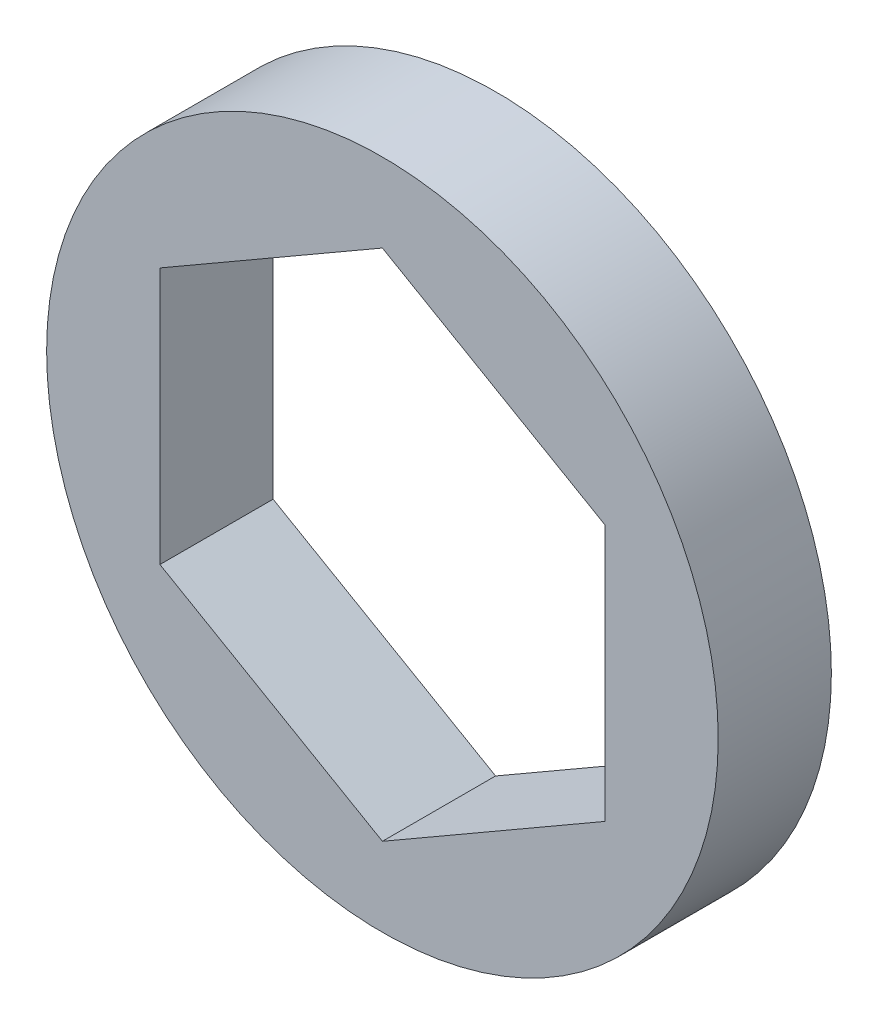
SolidWorks part; units mm, degrees
material "PET"
ref_plane "Front Plane" through (0, 0, 0) normal (0, 0, 1) x (1, 0, 0)
ref_plane "Top Plane" through (0, 0, 0) normal (0, 1, 0) x (1, 0, 0)
ref_plane "Right Plane" through (0, 0, 0) normal (1, 0, 0) x (0, 0, -1)
sketch "Sketch1" plane through (0, 0, 0) normal (0, 0, 1) x (1, 0, 0)
  line L1 (6.731, 3.8861) -> (0, 7.7723)
  line L2 (0, 7.7723) -> (-6.731, 3.8861)
  line L3 (-6.731, 3.8861) -> (-6.731, -3.8861)
  line L4 (-6.731, -3.8861) -> (0, -7.7723)
  line L5 (0, -7.7723) -> (6.731, -3.8861)
  line L6 (6.731, -3.8861) -> (6.731, 3.8861)
  circle A0 centre (0, 0) radius 6.731 construction
  circle A1 centre (0, 0) radius 10.16
  dimension "D1" = 13.462
  dimension "D2" = 20.32
extrude "Boss-Extrude1" add sketch "Sketch1" along normal blind 3.4239
